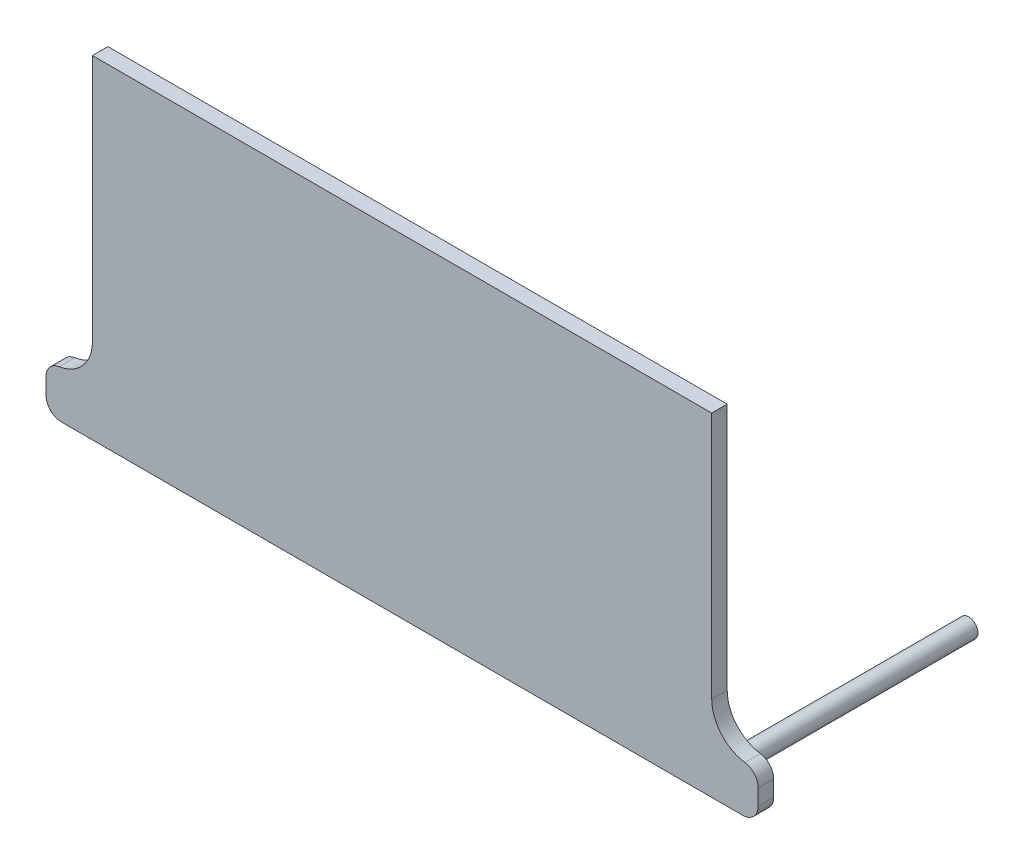
SolidWorks part; units mm, degrees
ref_plane "Front Plane" through (0, 0, 0) normal (0, 0, 1) x (1, 0, 0)
ref_plane "Top Plane" through (0, 0, 0) normal (0, 1, 0) x (1, 0, 0)
ref_plane "Right Plane" through (0, 0, 0) normal (1, 0, 0) x (0, 0, -1)
sketch "Sketch1" plane through (0, 0, 0) normal (0, 0, 1) x (1, 0, 0)
  line L0 (-200, -107.5) -> (-230, -107.5)
  line L1 (-200, 107.5) -> (200, 107.5)
  line L2 (-200, 107.5) -> (-200, -77.5)
  line L3 (-200, -107.5) -> (200, -107.5)
  line L4 (200, 107.5) -> (200, -77.5)
  line L5 (-200, 107.5) -> (200, -107.5) construction
  line L6 (-200, -107.5) -> (200, 107.5) construction
  line L7 (-230, -107.5) -> (-230, -77.5)
  line L8 (-230, -77.5) -> (-200, -77.5)
  line L9 (200, -107.5) -> (230, -107.5)
  line L10 (230, -107.5) -> (230, -77.5)
  line L11 (230, -77.5) -> (200, -77.5)
  line L12 (-200, -77.5) -> (-200, -107.5) construction
  line L13 (200, -107.5) -> (200, -77.5) construction
  point P0 (0, 0)
  dimension "D1" = 400
  dimension "D2" = 215
  dimension "D3" = 30
  dimension "D4" = 30
extrude "Boss-Extrude1" add sketch "Sketch1" along normal mid plane 10
fillet "Fillet1" radius 25 2 edges at (200, -77.5, 0) (-200, -77.5, 0)
sketch "Sketch2" plane through (0, 0, -5) normal (0, 0, -1) x (-1, 0, 0)
  circle A0 centre (-203, -92.5) radius 6
  circle A1 centre (203, -92.5) radius 6
  circle A2 centre (203, -92.5) radius 6 construction
  circle A3 centre (-203, -92.5) radius 6 construction
extrude "Boss-Extrude2" add sketch "Sketch2" along normal up to vertex (153 mm away)
fillet "Fillet2" radius 10 4 edges at (-230, -107.5, 0) (230, -107.5, 0) (-197, -92.5, -5) (209, -92.5, -5)
fillet "Fillet3" radius 10 2 edges at (-230, -77.5, 0) (230, -77.5, 0)
